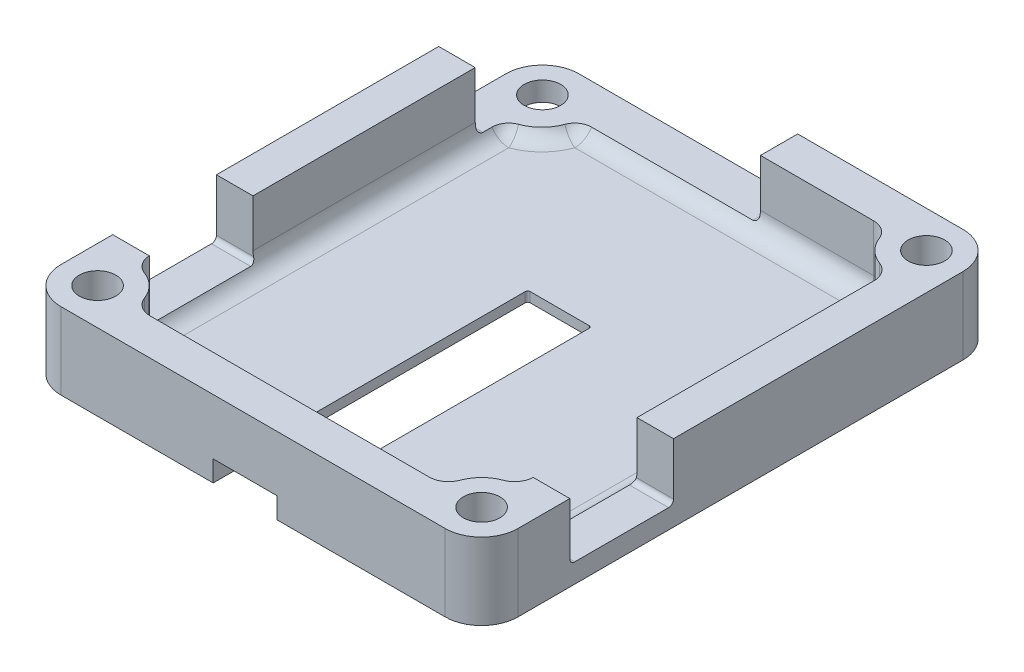
SolidWorks part; units mm, degrees
material "Nylon 6/10"
ref_plane "Front Plane" through (0, 0, 0) normal (0, 0, 1) x (1, 0, 0)
ref_plane "Top Plane" through (0, 0, 0) normal (0, 1, 0) x (1, 0, 0)
ref_plane "Right Plane" through (0, 0, 0) normal (1, 0, 0) x (0, 0, -1)
sketch "Sketch1" plane through (0, 0, 0) normal (0, 1, 0) x (1, 0, 0)
  line L1 (-29.1688, -45.1454) -> (33.8486, -45.1454)
  line L2 (-35.1632, -39.151) -> (-35.1632, 33.8486)
  line L3 (-29.1688, 39.843) -> (33.8486, 39.843)
  line L4 (39.843, -39.151) -> (39.843, 33.8486)
  line L5 (-39.9686, -39.9686) -> (39.843, 39.843) construction
  line L6 (-35.1632, 39.843) -> (39.843, -45.1454) construction
  line L7 (-29.1688, -39.151) -> (33.8486, -39.151) construction
  line L8 (-29.1688, -39.151) -> (-29.1688, 33.8486) construction
  line L9 (-29.1688, 33.8486) -> (33.8486, 33.8486) construction
  line L10 (33.8486, -39.151) -> (33.8486, 33.8486) construction
  line L11 (-29.1688, -39.151) -> (33.8486, 33.8486) construction
  line L12 (-29.1688, 33.8486) -> (33.8486, -39.151) construction
  arc A0 (-29.1688, 39.843) -> (-35.1632, 33.8486) centre (-29.1688, 33.8486) ccw
  arc A1 (-35.1632, -39.151) -> (-29.1688, -45.1454) centre (-29.1688, -39.151) ccw
  arc A2 (39.843, -39.151) -> (33.8486, -45.1454) centre (33.8486, -39.151) cw
  circle A3 centre (-29.1688, 33.8486) radius 2.9972
  circle A4 centre (33.8486, 33.8486) radius 2.9972
  circle A5 centre (33.8486, -39.151) radius 2.9972
  circle A6 centre (-29.1688, -39.151) radius 2.9972
  arc A7 (39.843, 33.8486) -> (33.8486, 39.843) centre (33.8486, 33.8486) ccw
  point P0 (0, 0)
  point P15 (2.3399, -2.6512)
  point P27 (0, 0)
  point P28 (0, 0)
  point P29 (0, 0)
  point P30 (0, 0)
  point P31 (0, 0)
  point P32 (0, 0)
  point P33 (0, 0)
  point P34 (-28.7739, -33.5876)
  dimension "D3" = 5.9944
  dimension "D4" = 5.9944
  dimension "D1" = 75.0062
  dimension "D2" = 84.9884
extrude "Boss-Extrude1" add sketch "Sketch1" along normal blind 12.573
sketch "Sketch5" plane through (0, 12.573, 0) normal (0, 1, 0) x (1, 0, 0)
  line L1 (-20.5667, -39.151) -> (25.2464, -39.151)
  line L2 (-29.1688, -30.5489) -> (-29.1688, 25.1361)
  line L3 (-20.5667, 33.7383) -> (25.2879, 33.7383)
  line L4 (33.8486, -30.5489) -> (33.8486, 25.2464)
  line L5 (-32.4486, -32.4486) -> (33.8486, 33.8486) construction
  line L6 (-29.1688, 33.7383) -> (33.8486, -39.151) construction
  arc A0 (-23.5453, 31.6626) -> (-27.0932, 28.1147) centre (-29.1688, 33.7383) cw
  arc A1 (28.2521, 31.7008) -> (31.7729, 28.225) centre (33.8486, 33.8486) ccw
  arc A2 (31.7729, -33.5275) -> (28.225, -37.0754) centre (33.8486, -39.151) ccw
  arc A4 (-29.1688, 39.843) -> (-35.1632, 33.8486) centre (-29.1688, 33.8486) ccw construction
  arc A5 (33.8486, -30.5489) -> (31.7729, -33.5275) centre (30.6736, -30.5489) cw
  arc A6 (28.225, -37.0754) -> (25.2464, -39.151) centre (25.2464, -35.976) cw
  arc A9 (33.8486, 25.2464) -> (31.7729, 28.225) centre (30.6736, 25.2464) ccw
  arc A10 (28.2521, 31.7008) -> (25.2879, 33.7383) centre (25.2879, 30.5633) ccw
  arc A11 (-29.1688, 25.1361) -> (-27.0932, 28.1147) centre (-25.9938, 25.1361) cw
  arc A12 (-20.5667, 33.7383) -> (-23.5453, 31.6626) centre (-20.5667, 30.5633) ccw
  arc A13 (-20.5667, -39.151) -> (-23.5453, -37.0754) centre (-20.5667, -35.976) cw
  circle A14 centre (33.8486, -39.151) radius 2.9972 construction
  arc A15 (-29.1688, -30.5489) -> (-27.0932, -33.5275) centre (-25.9938, -30.5489) ccw
  arc A16 (-23.5453, -37.0754) -> (-27.0932, -33.5275) centre (-29.1688, -39.151) ccw
  circle A17 centre (-29.1688, -39.151) radius 2.9972 construction
  arc A18 (-35.1632, -39.151) -> (-29.1688, -45.1454) centre (-29.1688, -39.151) ccw construction
  point P0 (0, 0)
  point P24 (0, 0)
  point P44 (0, 0)
  dimension "D1" = 3.175
  dimension "D2" = 3.175
extrude "Cut-Extrude3" cut sketch "Sketch5" against normal offset from surface 1.6002 and the other way through all up to face at (2.3399, 0, 2.6512)
fillet "Fillet1" radius 3.175 16 edges at (-22.3819, 1.6002, -33.1682) (-24.9302, 1.6002, -29.4996) (-28.5988, 1.6002, -26.9513) (-29.1688, 1.6002, 2.7064) (2.3399, 1.6002, 39.151) (27.0616, 1.6002, 38.581) (29.6099, 1.6002, 34.9124) (33.2785, 1.6002, 32.3641) (33.8486, 1.6002, 2.6512) (33.2785, 1.6002, -27.0616) (29.6372, 1.6002, -29.5827) (27.0864, 1.6002, -33.1798) (2.3606, 1.6002, -33.7383) (-28.5988, 1.6002, 32.3641) (-24.9302, 1.6002, 34.9124) (-22.3819, 1.6002, 38.581)
sketch "Sketch2" plane through (0, 0, 0) normal (0, 1, 0) x (1, 0, 0)
  line L0 (-29.1688, -45.1454) -> (33.8486, -45.1454) construction
  line L1 (-4.2006, -45.1454) -> (6.2642, -45.1454)
  line L2 (-4.2006, -45.1454) -> (-4.2006, 6.061)
  line L3 (-3.7942, 6.4674) -> (5.8578, 6.4674)
  line L4 (6.2642, -45.1454) -> (6.2642, 6.061)
  line L5 (-4.2006, -45.1454) -> (6.2642, 6.4674) construction
  line L6 (-4.2006, 6.4674) -> (6.2642, -45.1454) construction
  line L7 (-35.1632, 33.8486) -> (-35.1632, -39.151) construction
  arc A0 (6.2642, 6.061) -> (5.8578, 6.4674) centre (5.8578, 6.061) ccw
  arc A1 (-4.2006, 6.061) -> (-3.7942, 6.4674) centre (-3.7942, 6.061) cw
  point P0 (1.0318, -19.339)
  dimension "D4" = 0.4064
  dimension "D1" = 51.6128
  dimension "D2" = 10.4648
  dimension "D3" = 30.9626
extrude "Cut-Extrude1" cut sketch "Sketch2" along normal blind 3.429 and the other way through all
sketch "Sketch6" plane through (0, 12.573, 0) normal (0, 1, 0) x (1, 0, 0)
  line L0 (-35.1632, 33.8486) -> (-35.1632, -39.151) construction
  line L1 (-35.1632, -30.6674) -> (39.843, -30.6674)
  line L2 (-35.1632, -30.6674) -> (-35.1632, -13.6494)
  line L3 (-35.1632, -13.6494) -> (39.843, -13.6494)
  line L4 (39.843, -30.6674) -> (39.843, -13.6494)
  line L5 (-35.1632, -30.6674) -> (39.843, -13.6494) construction
  line L6 (-35.1632, -13.6494) -> (39.843, -30.6674) construction
  line L7 (39.843, -39.151) -> (39.843, 33.8486) construction
  line L8 (-29.1688, -45.1454) -> (33.8486, -45.1454) construction
  line L9 (-35.1632, 39.843) -> (6.7214, 39.843)
  line L10 (-35.1632, 39.843) -> (-35.1632, 22.825)
  line L11 (-35.1632, 22.825) -> (6.7214, 22.825)
  line L12 (6.7214, 39.843) -> (6.7214, 22.825)
  line L13 (33.8486, 39.843) -> (-29.1688, 39.843) construction
  point P0 (2.3399, -22.1584)
  dimension "D1" = 17.018
  dimension "D2" = 14.478
  dimension "D3" = 41.8846
extrude "Cut-Extrude4" cut sketch "Sketch6" against normal offset from surface (9.398 mm away) 3.175 contours L3 L4 L1 L2
fillet "Fillet2" radius 0.8128 6 edges at (36.6294, 3.175, 13.6494) (36.6281, 3.175, 30.6674) (-31.9484, 3.175, 30.6674) (-31.9497, 3.175, 13.6494) (-31.9497, 3.175, -22.825) (6.7214, 3.175, -36.5742)
